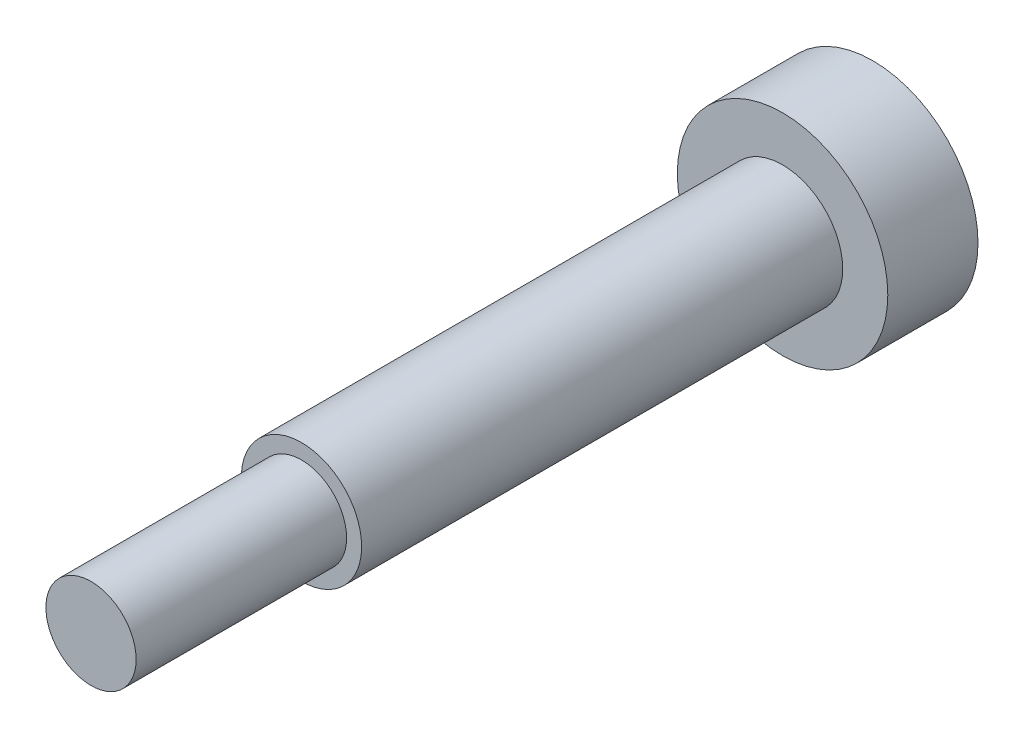
SolidWorks part; units mm, degrees
ref_plane "Front Plane" through (0, 0, 0) normal (0, 0, 1) x (1, 0, 0)
ref_plane "Top Plane" through (0, 0, 0) normal (0, 1, 0) x (1, 0, 0)
ref_plane "Right Plane" through (0, 0, 0) normal (1, 0, 0) x (0, 0, -1)
sketch "S01 - Socket head" plane through (0, 0, 0) normal (0, 0, 1) x (1, 0, 0)
  circle A0 centre (0, 0) radius 3.5
  dimension "D1" = 7
extrude "01 - Socket head" add sketch "S01 - Socket head" along normal blind 3 from offset 3
sketch "S02 - Ground shoulder" plane through (0, 0, 0) normal (0, 0, 1) x (1, 0, 0)
  circle A0 centre (0, 0) radius 2
  dimension "D1" = 4
extrude "02 - Ground shoulder" add sketch "S02 - Ground shoulder" along normal blind 16
sketch "S03 - Threaded tip major diameter" plane through (0, 0, 0) normal (0, 0, 1) x (1, 0, 0)
  circle A0 centre (0, 0) radius 1.5
  dimension "D1" = 3
extrude "03 - Threaded tip major diameter" add sketch "S03 - Threaded tip major diameter" along normal blind 7 from offset 16
sketch "S04 - Hexagonal drive" plane through (0, 0, 0) normal (0, 0, 1) x (1, 0, 0)
  line L0 (1.1547, 0) -> (0.5774, 1)
  line L1 (0.5774, 1) -> (-0.5774, 1)
  line L2 (-0.5774, 1) -> (-1.1547, 0)
  line L3 (-1.1547, 0) -> (-0.5774, -1)
  line L4 (-0.5774, -1) -> (0.5774, -1)
  line L5 (0.5774, -1) -> (1.1547, 0)
  dimension "D1" = 0.5774
  dimension "D2" = 1.1547
  dimension "D3" = 0.5774
  dimension "D4" = 1.1547
  dimension "D5" = 1
  dimension "D6" = 1
extrude "04 - Hexagonal drive" cut sketch "S04 - Hexagonal drive" along normal blind 2.14 from offset 3.1
